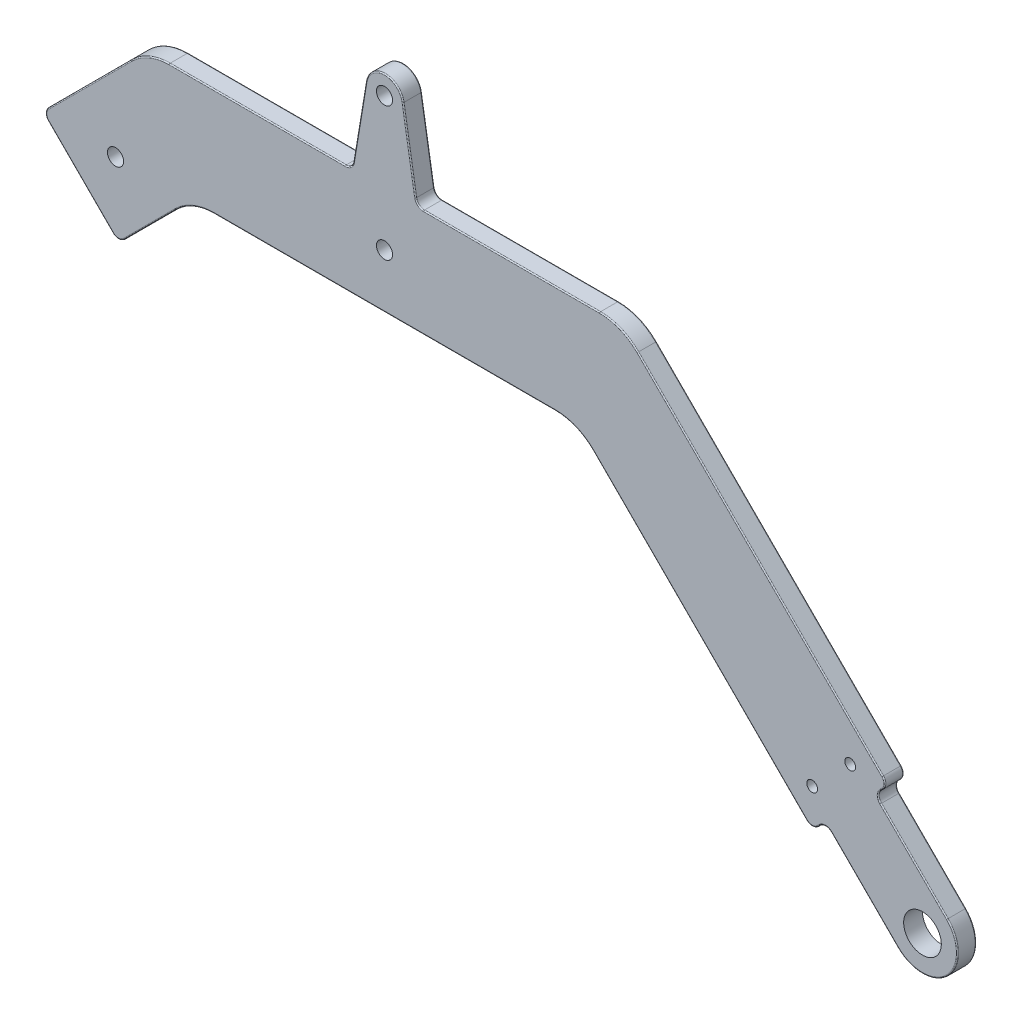
SolidWorks part; units mm, degrees
ref_plane "Front Plane" through (0, 0, 0) normal (0, 0, 1) x (1, 0, 0)
ref_plane "Top Plane" through (0, 0, 0) normal (0, 1, 0) x (1, 0, 0)
ref_plane "Right Plane" through (0, 0, 0) normal (1, 0, 0) x (0, 0, -1)
sketch "Sketch1" plane through (0, 0, 0) normal (0, 0, 1) x (1, 0, 0)
  line L0 (-100, 0) -> (100, 0) construction
  line L1 (-100, 0) -> (0, 100) construction
  line L2 (0, 100) -> (100, 0) construction
  line L3 (0, 0) -> (-50, 50) construction
  line L4 (-40, 60) -> (40, 60) construction
  line L5 (0, 100) -> (0, 60) construction
  circle A0 centre (-100, 0) radius 20
  circle A1 centre (0, 0) radius 20
  circle A2 centre (100, 0) radius 20
  point P4 (0, 0)
  dimension "D5" = 40
  dimension "D1" = 200
  dimension "D2" = 90
  dimension "D3" = 90
  dimension "D4" = 80
sketch "Sketch2" plane through (0, 0, 0) normal (0, 0, 1) x (1, 0, 0)
  line L0 (-56.5165, 43.4835) -> (-40, 60) construction
  line L1 (-100, 0) -> (0, 100) construction
  line L2 (-40, 60) -> (40, 60) construction
  line L3 (40, 60) -> (86.565, 13.435) construction
  line L4 (0, 100) -> (100, 0) construction
  line L5 (-49.4454, 36.4124) -> (-35.8579, 50)
  line L6 (-35.8579, 50) -> (35.8579, 50)
  line L7 (35.8579, 50) -> (79.4939, 6.364)
  line L8 (-63.5876, 50.5546) -> (-44.1421, 70)
  line L9 (-44.1421, 70) -> (44.1421, 70)
  line L10 (44.1421, 70) -> (93.636, 20.5061)
  line L11 (-63.5876, 50.5546) -> (-49.4454, 36.4124)
  line L12 (93.636, 20.5061) -> (79.4939, 6.364)
  line L13 (91.1612, 18.0312) -> (104.5962, 4.5962)
  line L14 (81.9688, 8.8388) -> (95.4038, -4.5962)
  line L15 (75.9584, 9.8995) -> (90.1005, 24.0416) construction
  line L16 (0, 100) -> (0, 60) construction
  line L17 (-6, 70) -> (-3.4532, 85.4203)
  line L18 (6, 70) -> (3.4532, 85.4203)
  circle A0 centre (100, 0) radius 3.5
  circle A1 centre (100, 0) radius 10 construction
  arc A2 (95.4038, -4.5962) -> (104.5962, 4.5962) centre (100, 0) ccw
  circle A3 centre (79.4939, 13.435) radius 1
  circle A4 centre (100, 0) radius 6.5 construction
  circle A5 centre (86.565, 20.5061) radius 1
  circle A6 centre (0, 60) radius 1.5
  circle A7 centre (0, 84.85) radius 1.5
  arc A8 (3.4532, 85.4203) -> (-3.4532, 85.4203) centre (0, 84.85) ccw
  circle A9 centre (-50, 50) radius 1.5
  circle A10 centre (0, 84.85) radius 3.5 construction
  point P25 (106.5, 0)
  point P47 (3.5, 82)
  dimension "D4" = 7
  dimension "D5" = 20
  dimension "D9" = 2
  dimension "D12" = 3
  dimension "D17" = 3
  dimension "D3" = 27.5
  dimension "D7" = 19
  dimension "D8" = 5
  dimension "D10" = 5
  dimension "D11" = 5
  dimension "D13" = 14.85
  dimension "D15" = 6
  dimension "D16" = 6
  dimension "D1" = 10
  dimension "D2" = 10
  dimension "D6" = 3
  dimension "D14" = 2
sketch "Sketch3" plane through (0, 0, 0) normal (0, 0, 1) x (1, 0, 0)
  line L0 (-100, 0) -> (100, 0) construction
  line L1 (-86.565, 13.435) -> (-50, 50) construction
  line L2 (-100, 0) -> (0, 100) construction
  line L3 (-50, 50) -> (-13.435, 13.435) construction
  line L4 (0, 0) -> (-50, 50) construction
  line L5 (-79.4939, 6.364) -> (-50, 35.8579)
  line L6 (-50, 35.8579) -> (-20.5061, 6.364)
  line L7 (-93.636, 20.5061) -> (-50, 64.1421)
  line L8 (-50, 64.1421) -> (-6.364, 20.5061)
  line L9 (-6.364, 20.5061) -> (-20.5061, 6.364)
  line L10 (-93.636, 20.5061) -> (-79.4939, 6.364)
  line L11 (-91.1612, 18.0312) -> (-104.5962, 4.5962)
  line L12 (-81.9688, 8.8388) -> (-95.4038, -4.5962)
  line L13 (-4.6576, -4.534) -> (-17.8509, 9.0191)
  line L14 (4.5962, 4.5962) -> (-8.8388, 18.0312)
  line L15 (-90.1005, 24.0416) -> (-75.9584, 9.8995) construction
  line L16 (-24.0416, 9.8995) -> (-9.8995, 24.0416) construction
  circle A0 centre (-100, 0) radius 3.5
  circle A1 centre (0, 0) radius 3.5
  circle A2 centre (-100, 0) radius 10 construction
  circle A3 centre (0, 0) radius 10 construction
  arc A4 (-4.6576, -4.534) -> (4.5962, 4.5962) centre (0, 0) ccw
  arc A5 (-104.5962, 4.5962) -> (-95.4038, -4.5962) centre (-100, 0) ccw
  circle A6 centre (0, 0) radius 20 construction
  circle A7 centre (-100, 0) radius 6.5 construction
  circle A8 centre (-86.565, 20.5061) radius 1
  circle A9 centre (0, 0) radius 6.5 construction
  circle A10 centre (-79.4939, 13.435) radius 1
  circle A11 centre (-20.5061, 13.435) radius 1
  circle A12 centre (-13.435, 20.5061) radius 1
  point P28 (-93.5, 0)
  point P36 (6.5, 0)
  dimension "D1" = 20
  dimension "D2" = 7
  dimension "D8" = 2
  dimension "D12" = 2
  dimension "D6" = 19
  dimension "D7" = 19
  dimension "D9" = 5
  dimension "D10" = 5
  dimension "D11" = 5
  dimension "D13" = 5
  dimension "D14" = 5
  dimension "D15" = 5
  dimension "D3" = 3
  dimension "D4" = 10
  dimension "D5" = 10
sketch "Sketch4" plane through (0, 0, 0) normal (0, 0, 1) x (1, 0, 0)
  line L0 (-57.5, 93.35) -> (57.5, 93.35)
  line L1 (4, 60) -> (4, 70)
  line L2 (57.5, 93.35) -> (57.5, 83.35)
  line L3 (57.5, 83.35) -> (44.1421, 70)
  line L4 (-44.1421, 70) -> (-57.5, 83.35)
  line L5 (-57.5, 83.35) -> (-57.5, 93.35)
  line L6 (-44.1421, 70) -> (44.1421, 70) construction
  line L7 (-4, 60) -> (-4, 70)
  line L8 (-22.5, 84.85) -> (22.5, 84.85) construction
  line L9 (-22.5, 89.35) -> (22.5, 89.35)
  line L10 (-22.5, 80.35) -> (22.5, 80.35)
  circle A2 centre (0, 60) radius 4
  arc A3 (-4, 60) -> (4, 60) centre (0, 60) ccw
  arc A4 (-22.5, 89.35) -> (-22.5, 80.35) centre (-22.5, 84.85) ccw
  arc A5 (22.5, 80.35) -> (22.5, 89.35) centre (22.5, 84.85) ccw
  point P4 (0, 100)
  point P14 (0, 84.85)
  point P27 (0, 93.35)
  dimension "D5" = 9
  dimension "D1" = 115
  dimension "D2" = 10
  dimension "D4" = 45
  dimension "D6" = 4
  dimension "D3" = 2.5
sketch "Sketch5" plane through (0, 0, 0) normal (0, 0, 1) x (1, 0, 0)
  line L0 (91.1612, 18.0312) -> (104.5962, 4.5962) construction
  line L1 (81.9688, 8.8388) -> (95.4038, -4.5962) construction
  line L2 (-6, 70) -> (-3.4532, 85.4203) construction
  line L3 (6, 70) -> (3.4532, 85.4203) construction
  line L4 (91.1612, 18.0312) -> (104.5962, 4.5962)
  line L5 (81.9688, 8.8388) -> (95.4038, -4.5962)
  line L6 (-6, 70) -> (-3.4532, 85.4203)
  line L7 (6, 70) -> (3.4532, 85.4203)
  line L8 (93.636, 20.5061) -> (44.1421, 70)
  line L9 (79.4939, 6.364) -> (93.636, 20.5061)
  line L10 (35.8579, 50) -> (79.4939, 6.364)
  line L11 (-35.8579, 50) -> (35.8579, 50)
  line L12 (-49.4454, 36.4124) -> (-35.8579, 50)
  line L13 (-63.5876, 50.5546) -> (-49.4454, 36.4124)
  line L14 (-44.1421, 70) -> (-63.5876, 50.5546)
  line L15 (44.1421, 70) -> (-44.1421, 70)
  line L16 (93.636, 20.5061) -> (44.1421, 70)
  line L17 (79.4939, 6.364) -> (81.9688, 8.8388)
  line L18 (35.8579, 50) -> (79.4939, 6.364)
  line L19 (-35.8579, 50) -> (35.8579, 50)
  line L20 (-49.4454, 36.4124) -> (-35.8579, 50)
  line L21 (-63.5876, 50.5546) -> (-49.4454, 36.4124)
  line L22 (-44.1421, 70) -> (-63.5876, 50.5546)
  line L23 (44.1421, 70) -> (6, 70)
  line L24 (-6, 70) -> (-44.1421, 70)
  line L25 (91.1612, 18.0312) -> (93.636, 20.5061)
  arc A0 (95.4038, -4.5962) -> (104.5962, 4.5962) centre (100, 0) ccw construction
  circle A1 centre (100, 0) radius 3.5
  circle A2 centre (100, 0) radius 3.5
  circle A3 centre (0, 84.85) radius 1.5
  circle A4 centre (0, 84.85) radius 1.5
  circle A5 centre (0, 60) radius 1.5
  circle A6 centre (0, 60) radius 1.5
  circle A7 centre (86.565, 20.5061) radius 1
  circle A8 centre (86.565, 20.5061) radius 1
  circle A9 centre (79.4939, 13.435) radius 1
  circle A10 centre (79.4939, 13.435) radius 1
  circle A11 centre (-50, 50) radius 1.5
  circle A12 centre (-50, 50) radius 1.5
  arc A13 (3.4532, 85.4203) -> (-3.4532, 85.4203) centre (0, 84.85) ccw construction
  arc A14 (95.4038, -4.5962) -> (104.5962, 4.5962) centre (100, 0) ccw
  arc A15 (3.4532, 85.4203) -> (-3.4532, 85.4203) centre (0, 84.85) ccw
  dimension "D1" = 0
  dimension "D2" = 0
  dimension "D3" = 0
  dimension "D4" = 0
  dimension "D5" = 0
  dimension "D6" = 0
  dimension "D7" = 0
extrude "Boss-Extrude1" add sketch "Sketch5" along normal blind 3.5
fillet "Fillet1" radius 10 4 edges at (35.8579, 50, 1.75) (-35.8579, 50, 1.75) (-44.1421, 70, 1.75) (44.1421, 70, 1.75)
fillet "Fillet2" radius 1.5 8 edges at (81.9688, 8.8388, 1.75) (79.4939, 6.364, 1.75) (91.1612, 18.0312, 1.75) (93.636, 20.5061, 1.75) (-49.4454, 36.4124, 1.75) (-63.5876, 50.5546, 1.75) (6, 70, 1.75) (-6, 70, 1.75)
fillet "Fillet3" radius 0.2 56 edges at (6.3022, 70.3562, 3.5) (23.6363, 70, 3.5) (43.8268, 69.2388, 3.5) (69.8232, 44.3189, 3.5) (93.0147, 20.5061, 3.5) (92.3986, 19.2687, 3.5) (91.7825, 18.0312, 3.5) (98.409, 10.7834, 3.5) (104.5962, -4.5962, 3.5) (89.2166, 1.591, 3.5) (81.9688, 8.2175, 3.5) (80.7313, 7.6014, 3.5) (79.4939, 6.9853, 3.5) (58.61, 27.2478, 3.5) (35.5426, 49.2388, 3.5) (0, 50, 3.5) (-35.5426, 49.2388, 3.5) (-43.5858, 42.2721, 3.5) (-49.4454, 37.0337, 3.5) (-56.5165, 43.4835, 3.5) (-62.9663, 50.5546, 3.5) (-54.799, 59.3431, 3.5) (-43.8268, 69.2388, 3.5) (-23.6363, 70, 3.5) (-6.3022, 70.3562, 3.5) (-4.6229, 78.3379, 3.5) (0, 88.35, 3.5) (43.8268, 69.2388, 0) (69.8232, 44.3189, 0) (93.0147, 20.5061, 0) (92.3986, 19.2687, 0) (91.7825, 18.0312, 0) (98.409, 10.7834, 0) (104.5962, -4.5962, 0) (89.2166, 1.591, 0) (81.9688, 8.2175, 0) (80.7313, 7.6014, 0) (79.4939, 6.9853, 0) (58.61, 27.2478, 0) (35.5426, 49.2388, 0) (0, 50, 0) (-35.5426, 49.2388, 0) (-43.5858, 42.2721, 0) (-49.4454, 37.0337, 0) (-56.5165, 43.4835, 0) (-62.9663, 50.5546, 0) (-54.799, 59.3431, 0) (-43.8268, 69.2388, 0) (-23.6363, 70, 0) (-6.3022, 70.3562, 0) (-4.6229, 78.3379, 0) (0, 88.35, 0) (4.6229, 78.3379, 0) (6.3022, 70.3562, 0) (4.6229, 78.3379, 3.5) (23.6363, 70, 0)
